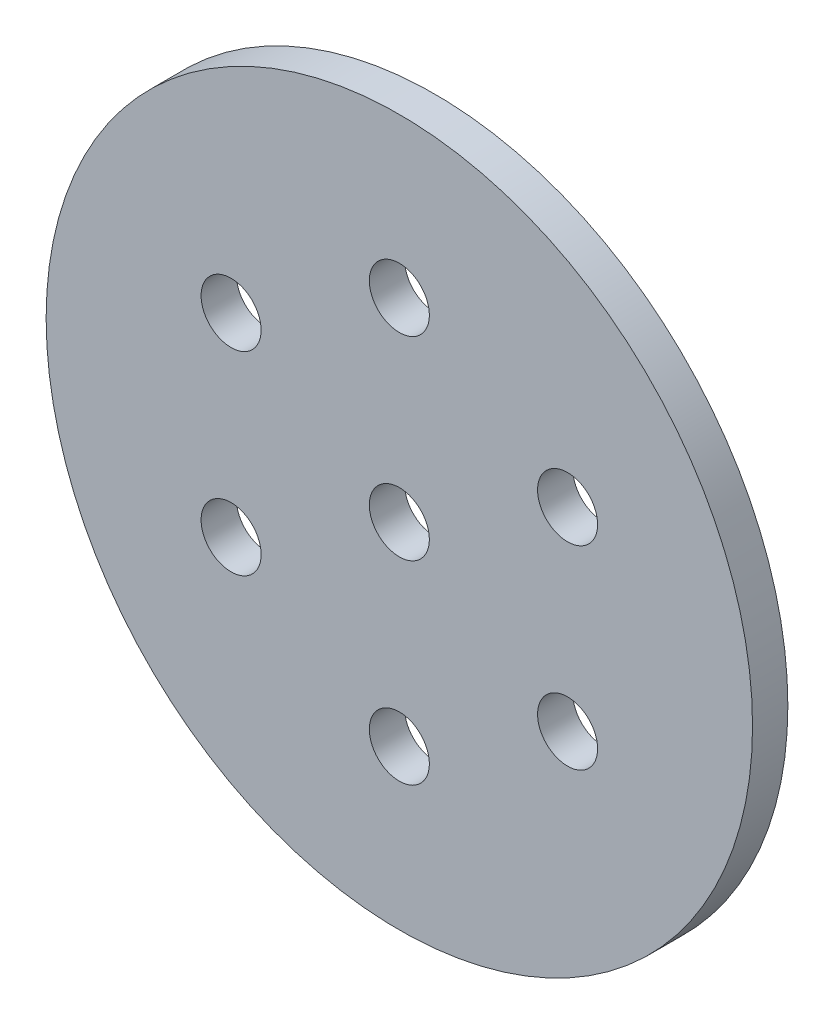
SolidWorks part; units mm, degrees
ref_plane "Front Plane" through (0, 0, 0) normal (0, 0, 1) x (1, 0, 0)
ref_plane "Top Plane" through (0, 0, 0) normal (0, 1, 0) x (1, 0, 0)
ref_plane "Right Plane" through (0, 0, 0) normal (1, 0, 0) x (0, 0, -1)
sketch "Sketch1" plane through (0, 0, 0) normal (0, 0, 1) x (1, 0, 0)
  circle A0 centre (0, 0) radius 100
  circle A1 centre (0, 0) radius 8.5
  circle A2 centre (0, 55) radius 8.5
  circle A3 centre (47.6314, 27.5) radius 8.5
  circle A4 centre (47.6314, -27.5) radius 8.5
  circle A5 centre (0, -55) radius 8.5
  circle A6 centre (-47.6314, -27.5) radius 8.5
  circle A7 centre (-47.6314, 27.5) radius 8.5
  point P7 (0, 0)
  point P8 (0, 0)
  point P18 (0, 0)
  dimension "D1" = 200
  dimension "D2" = 17
  dimension "D3" = 17
  dimension "D5" = 55
  dimension "D4" = 6
extrude "Boss-Extrude1" add sketch "Sketch1" along normal blind 10
